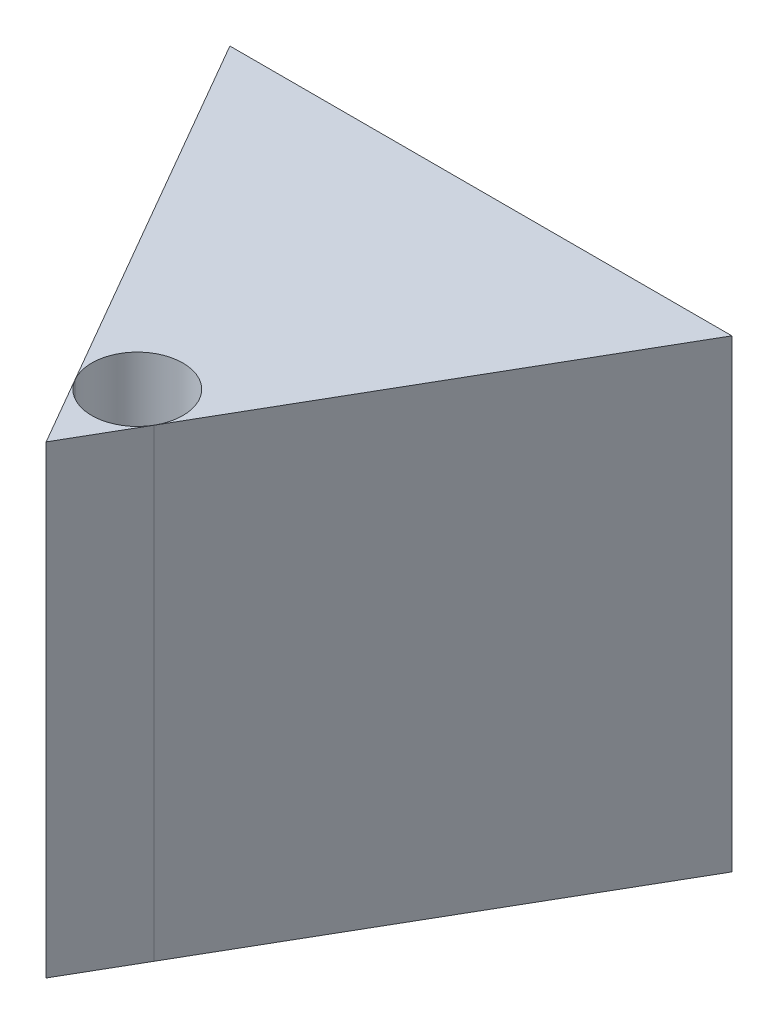
SolidWorks part; units mm, degrees
ref_plane "Front Plane" through (0, 0, 0) normal (0, 0, 1) x (1, 0, 0)
ref_plane "Top Plane" through (0, 0, 0) normal (0, 1, 0) x (1, 0, 0)
ref_plane "Right Plane" through (0, 0, 0) normal (1, 0, 0) x (0, 0, -1)
sketch "Sketch1" plane through (0, 0, 0) normal (0, 1, 0) x (1, 0, 0)
  line L0 (-108.1177, 0) -> (108.1177, 0)
  line L1 (108.1177, 0) -> (0, -187.2653)
  line L2 (0, -187.2653) -> (-108.1177, 0)
  line L3 (0, 129.8776) -> (0, -286.9388) construction
  circle A0 centre (0, -148) radius 19.6327
  dimension "D2" = 39.2653
  dimension "D1" = 148
extrude "Boss-Extrude1" add sketch "Sketch1" along normal blind 200 contours L0 L3 A0 L1 | L3 L0 L2 A0 | L3 A0 L2 | A0 L3 L1
